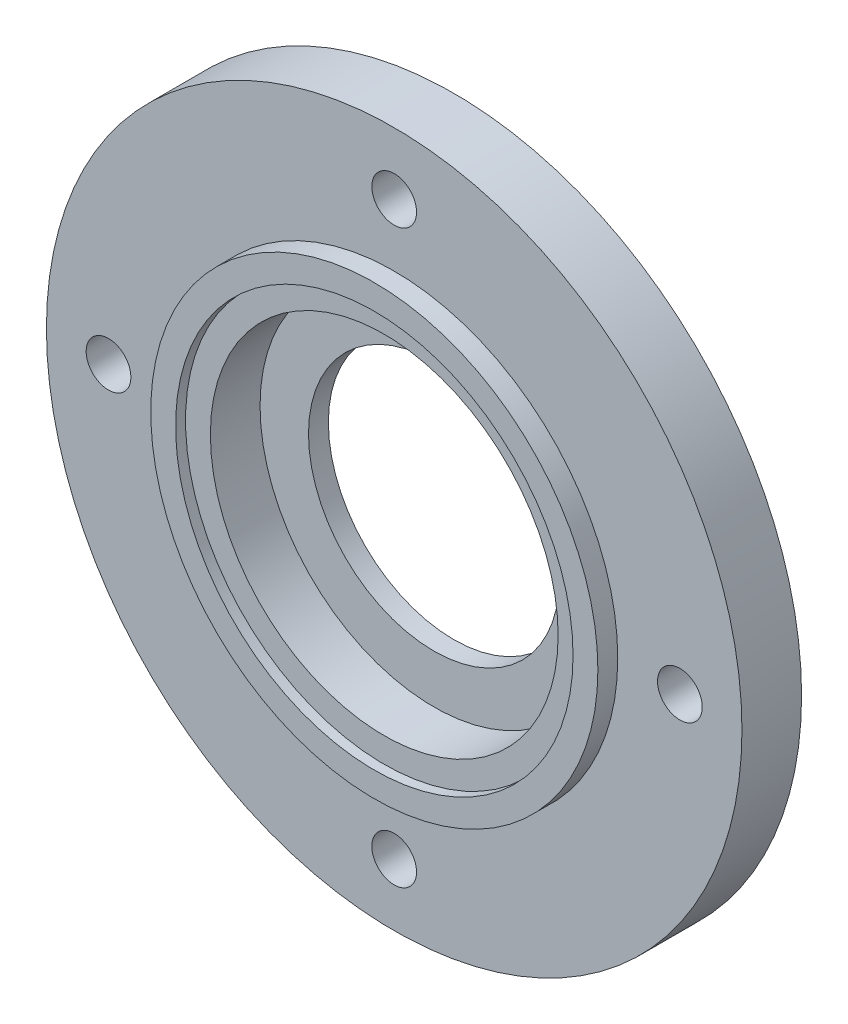
SolidWorks part; units mm, degrees
ref_plane "Front" through (0, 0, 0) normal (0, 0, 1) x (1, 0, 0)
ref_plane "Top" through (0, 0, 0) normal (0, 1, 0) x (1, 0, 0)
ref_plane "Right" through (0, 0, 0) normal (1, 0, 0) x (0, 0, -1)
sketch "Sketch1" plane through (0, 0, 0) normal (0, 0, 1) x (1, 0, 0)
  circle A0 centre (0, 0) radius 70
  circle A1 centre (0, 0) radius 57.5 construction
  circle A2 centre (0, 57.5) radius 4.5
  circle A3 centre (57.5, 0) radius 4.5
  circle A4 centre (0, -57.5) radius 4.5
  circle A5 centre (-57.5, 0) radius 4.5
  dimension "D1" = 140
  dimension "D2" = 115
  dimension "D3" = 9
  dimension "D4" = 4
extrude "Boss-Extrude1" add sketch "Sketch1" along normal blind 16
sketch "Sketch2" plane through (0, 0, 16) normal (0, 0, 1) x (1, 0, 0)
  circle A0 centre (0, 0) radius 70
  circle A1 centre (0, 0) radius 45
  dimension "D1" = 90
extrude "Cut-Extrude1" cut sketch "Sketch2" against normal blind 4
sketch "Sketch3" plane through (0, 0, 16) normal (0, 0, 1) x (1, 0, 0)
  circle A0 centre (0, 0) radius 40
  dimension "D1" = 80
extrude "Cut-Extrude2" cut sketch "Sketch3" against normal blind 2
sketch "Sketch4" plane through (0, 0, 14) normal (0, 0, 1) x (1, 0, 0)
  circle A0 centre (0, 0) radius 25.25
  dimension "D1" = 50.5
extrude "Cut-Extrude3" cut sketch "Sketch4" against normal blind 24
sketch "Sketch7" plane through (0, 0, 14) normal (0, 0, 1) x (1, 0, 0)
  circle A0 centre (0, 0) radius 35
  dimension "D1" = 70
extrude "Cut-Extrude5" cut sketch "Sketch7" against normal blind 10
sketch "Sketch8" plane through (0, 0, 12) normal (0, 0, 1) x (1, 0, 0)
  line L0 (-57.5, 0) -> (0, 57.5) construction
sketch "Sketch9" plane through (0, 0, 0) normal (0, 0, -1) x (-1, 0, 0)
  line L0 (0, 57.5) -> (57.5, 0) construction
ref_plane "Plane1" through (-28.75, 28.75, 0) normal (-0.7071, 0.7071, 0) x (0, 0, 1)
